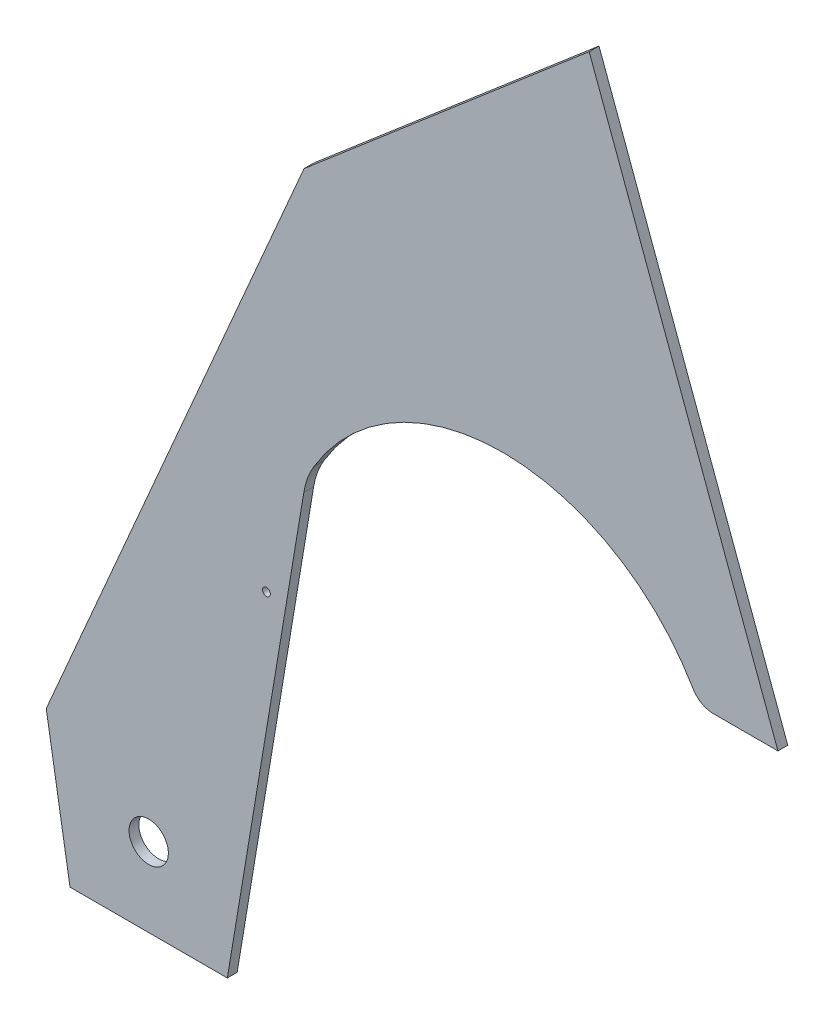
SolidWorks part; units mm, degrees
ref_plane "Front Plane" through (0, 0, 0) normal (0, 0, 1) x (1, 0, 0)
ref_plane "Top Plane" through (0, 0, 0) normal (0, 1, 0) x (1, 0, 0)
ref_plane "Right Plane" through (0, 0, 0) normal (1, 0, 0) x (0, 0, -1)
sketch "Sketch1" plane through (0, 0, 0) normal (0, 0, 1) x (1, 0, 0)
  line L1 (0, 0) -> (50.8, 0)
  line L6 (-25.4, 152.4) -> (0, 0)
  line L7 (76.2, 152.4) -> (50.8, 0)
  line L8 (203.2, 152.4) -> (228.6, 152.4)
  line L12 (-25.4, 152.4) -> (167.6422, 317.4779)
  line L14 (228.6, 152.4) -> (167.6422, 317.4779)
  circle A0 centre (25.4, 25.4) radius 6.35
  arc A1 (76.2, 152.4) -> (203.2, 152.4) centre (139.7, 120.3718) cw
  point P1 (0, 0)
  point P2 (0, 0)
  point P11 (0, 0)
  dimension "D5" = 12.7
  dimension "D4" = 127
  dimension "D8" = 71.12
  dimension "D1" = 165.0779
  dimension "D2" = 152.4
  dimension "D3" = 25.4
  dimension "D6" = 254
  dimension "D7" = 101.6
  dimension "D9" = 25.4
  dimension "D10" = 175.9732
  dimension "D11" = 317.4779
extrude "Boss-Extrude1" add sketch "Sketch1" along normal blind 3.175
sketch "Sketch4" plane through (0, 0, 3.175) normal (0, 0, 1) x (1, 0, 0)
  line L10 (86.2394, 263.4327) -> (-16.1852, 26.4504)
  line L11 (-16.1852, 26.4504) -> (-107.2293, 193.8108)
  line L12 (-107.2293, 193.8108) -> (86.2394, 263.4327)
extrude "Cut-Extrude3" cut sketch "Sketch4" against normal through all
fillet "Fillet1" radius 7.62 1 edges at (203.2, 152.4, 1.5875)
fillet "Fillet4" radius 25.4 1 edges at (76.2, 152.4, 1.5875)
sketch "Sketch5" plane through (0, 0, 0) normal (0, 0, -1) x (-1, 0, 0)
  line L0 (0, 0) -> (-50.8, 0) construction
  line L1 (-50.8, 0) -> (-75.4927, 148.1562) construction
  circle A0 centre (-63.4124, 114.3) radius 1.27
  dimension "D1" = 2.54
  dimension "D2" = 114.3
  dimension "D3" = 6.35
extrude "Cut-Extrude4" cut sketch "Sketch5" against normal through all
